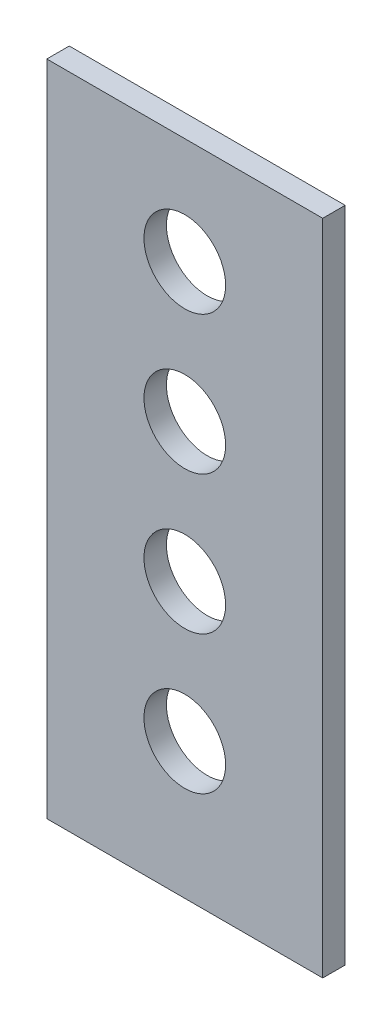
SolidWorks part; units mm, degrees
ref_plane "Спереди" through (0, 0, 0) normal (0, 0, 1) x (1, 0, 0)
ref_plane "Сверху" through (0, 0, 0) normal (0, 1, 0) x (1, 0, 0)
ref_plane "Справа" through (0, 0, 0) normal (1, 0, 0) x (0, 0, -1)
sketch "Эскиз1" plane through (0, 0, 0) normal (0, 0, 1) x (1, 0, 0)
  line L1 (0, 0) -> (67.5862, 0)
  line L2 (0, 0) -> (0, -161.1649)
  line L3 (0, -161.1649) -> (67.5862, -161.1649)
  line L4 (67.5862, 0) -> (67.5862, -161.1649)
  circle A0 centre (33.7931, -26.109) radius 10
  circle A1 centre (33.7931, -60.0206) radius 10
  circle A2 centre (33.7931, -93.9323) radius 10
  circle A3 centre (33.7931, -127.8439) radius 10
extrude "Вытянуть1" add sketch "Эскиз1" along normal blind 5.5
